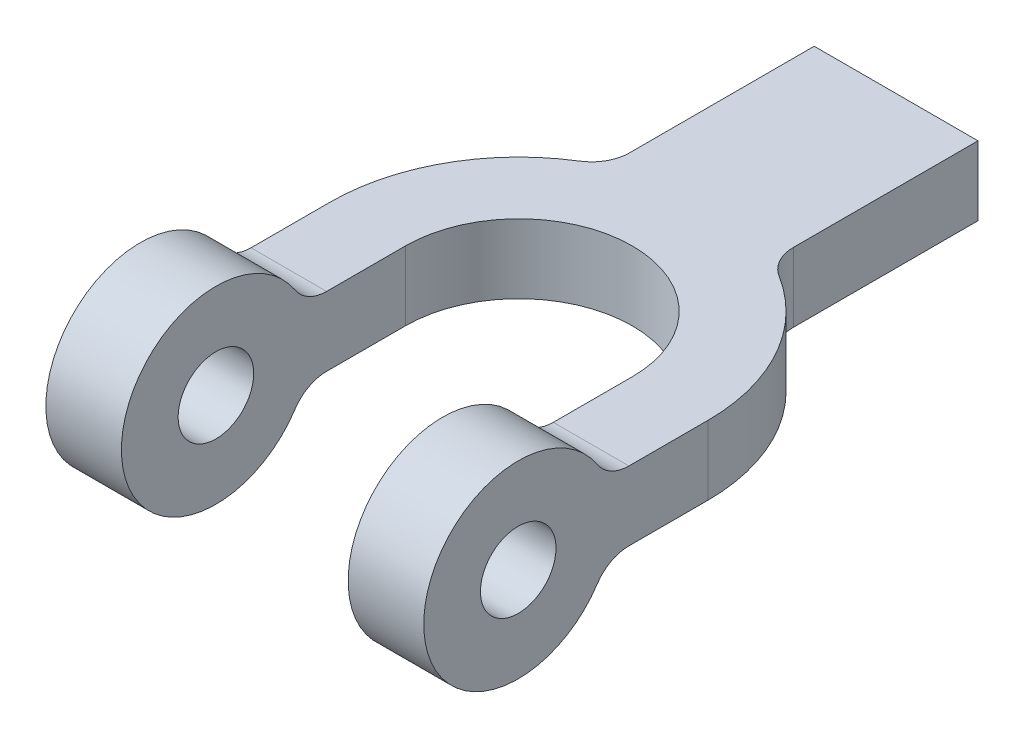
SolidWorks part; units mm, degrees
ref_plane "Front Plane" through (0, 0, 0) normal (0, 0, 1) x (1, 0, 0)
ref_plane "Top Plane" through (0, 0, 0) normal (0, 1, 0) x (1, 0, 0)
ref_plane "Right Plane" through (0, 0, 0) normal (1, 0, 0) x (0, 0, -1)
sketch "Sketch2" plane through (0, 0, 0) normal (0, 1, 0) x (1, 0, 0)
  line L1 (100, -175) -> (-100, -175)
  line L2 (100, -175) -> (100, 175)
  line L3 (100, 175) -> (-100, 175)
  line L4 (-100, -175) -> (-100, 175)
  line L5 (100, -175) -> (-100, 175) construction
  line L6 (100, 175) -> (-100, -175) construction
  point P0 (0, 0)
  dimension "D1" = 200
  dimension "D2" = 350
extrude "Boss-Extrude1" add sketch "Sketch2" along normal blind 100
sketch "Sketch3" plane through (0, 100, 0) normal (0, 1, 0) x (1, 0, 0)
  line L0 (0, 0) -> (0, -175) construction
  line L1 (-100, -175) -> (100, -175) construction
  line L2 (0, -175) -> (0, 175) construction
  line L3 (100, 175) -> (-100, 175) construction
  line L4 (-43.3476, 175) -> (-43.3476, 77.2727)
  line L5 (43.3476, 175) -> (43.3476, 77.2727)
  circle A0 centre (0, -24.6443) radius 60
  arc A1 (-52.7897, 60.2865) -> (52.7897, 60.2865) centre (0, -24.6443) ccw
  arc A2 (-43.3476, 77.2727) -> (-52.7897, 60.2865) centre (-63.3476, 77.2727) cw
  arc A3 (52.7897, 60.2865) -> (43.3476, 77.2727) centre (63.3476, 77.2727) cw
  point P16 (-43.3476, 65.4722)
  point P19 (43.3476, 65.4722)
  point P20 (-292.8414, -78.9371)
  dimension "D1" = 120
  dimension "D2" = 20
  dimension "D3" = 20
sketch "Sketch4" plane through (0, 100, 0) normal (0, 1, 0) x (1, 0, 0)
  line L0 (43.3476, 175) -> (43.3476, 77.2727) construction
  line L1 (-43.3476, 175) -> (-43.3476, 77.2727) construction
  line L2 (43.3476, 175) -> (43.3476, 77.2727)
  line L3 (-43.3476, 175) -> (-43.3476, 77.2727)
  line L4 (-60, -24.6443) -> (-60, -175)
  line L5 (-100, -175) -> (100, -175) construction
  line L6 (0, -24.6443) -> (0, -175) construction
  line L7 (60, -24.6443) -> (60, -175)
  line L8 (-100, 175) -> (-100, -175) construction
  line L9 (100, -175) -> (100, 175) construction
  line L10 (-100, 175) -> (-100, -175)
  line L11 (100, -175) -> (100, 175)
  line L12 (100, 175) -> (-100, 175) construction
  line L13 (100, 175) -> (-100, 175)
  line L14 (-100, -175) -> (100, -175)
  arc A0 (43.3476, 77.2727) -> (52.7897, 60.2865) centre (63.3476, 77.2727) ccw construction
  circle A1 centre (0, -24.6443) radius 60
  circle A2 centre (0, -24.6443) radius 60
  arc A3 (-52.7897, 60.2865) -> (52.7897, 60.2865) centre (0, -24.6443) ccw construction
  arc A4 (-52.7897, 60.2865) -> (-43.3476, 77.2727) centre (-63.3476, 77.2727) ccw construction
  arc A5 (43.3476, 77.2727) -> (52.7897, 60.2865) centre (63.3476, 77.2727) ccw
  arc A6 (-52.7897, 60.2865) -> (52.7897, 60.2865) centre (0, -24.6443) ccw
  arc A7 (-52.7897, 60.2865) -> (-43.3476, 77.2727) centre (-63.3476, 77.2727) ccw
  dimension "D1" = 0
extrude "Cut-Extrude3" cut sketch "Sketch4" against normal through all
sketch "Sketch5" plane through (100, 0, 0) normal (1, 0, 0) x (0, 0, -1)
  line L0 (-175, 100) -> (-175, 0) construction
  line L1 (-175, 50) -> (175, 50) construction
  line L2 (175, 0) -> (175, 100) construction
  line L3 (-66.42, 68.3195) -> (175, 68.3195)
  line L4 (-66.42, 31.6805) -> (175, 31.6805)
  line L5 (-175, 0) -> (-24.6443, 0) construction
  line L6 (77.2727, 100) -> (60.2865, 100) construction
  line L7 (60.2865, 100) -> (-124.6443, 100) construction
  line L8 (-24.6443, 0) -> (60.2865, 0) construction
  line L9 (175, 100) -> (77.2727, 100)
  line L10 (77.2727, 100) -> (77.2727, 0)
  line L11 (77.2727, 0) -> (175, 0)
  line L12 (175, 0) -> (175, 100)
  line L13 (175, 100) -> (77.2727, 100)
  line L14 (77.2727, 100) -> (77.2727, 0)
  line L15 (77.2727, 0) -> (175, 0)
  line L16 (175, 0) -> (175, 100)
  line L17 (60.2865, 0) -> (77.2727, 0) construction
  line L18 (-175, 0) -> (-24.6443, 0)
  line L19 (77.2727, 100) -> (60.2865, 100)
  line L20 (60.2865, 100) -> (-124.6443, 100)
  line L21 (-24.6443, 0) -> (60.2865, 0)
  line L22 (60.2865, 0) -> (77.2727, 0)
  arc A0 (-83.1572, 77.3711) -> (-83.1572, 22.6289) centre (-125, 50) ccw
  circle A1 centre (-125, 50) radius 20
  arc A2 (-66.42, 68.3195) -> (-83.1572, 77.3711) centre (-66.42, 88.3195) cw
  arc A3 (-66.42, 31.6805) -> (-83.1572, 22.6289) centre (-66.42, 11.6805) ccw
  point P5 (-175, 50)
  point P15 (-78.4769, 68.3195)
  point P18 (-78.4769, 31.6805)
  line M1 (-175, 0) -> (-24.6443, 0)
  line M2 (-24.6443, 0) -> (-24.6443, 100)
  line M3 (-24.6443, 100) -> (-175, 100)
  line M4 (-175, 100) -> (-175, 0)
  dimension "D1" = 100
  dimension "D2" = 40
  dimension "D3" = 20
  dimension "D4" = 20
  dimension "D5" = 0
extrude "Cut-Extrude4" cut sketch "Sketch5" against normal through all contours A0 M3 M4 | A1 L1 | L1 A1 | A0 M4 M1 | L4 A3 A0 L18 M2 | A2 L3 A0 M2 M3 | L19 L20 L3 L14 M2 | L21 L22 L14 L4 M2 | L15 L16 L4 L14 | L3 L16 L13 L14
